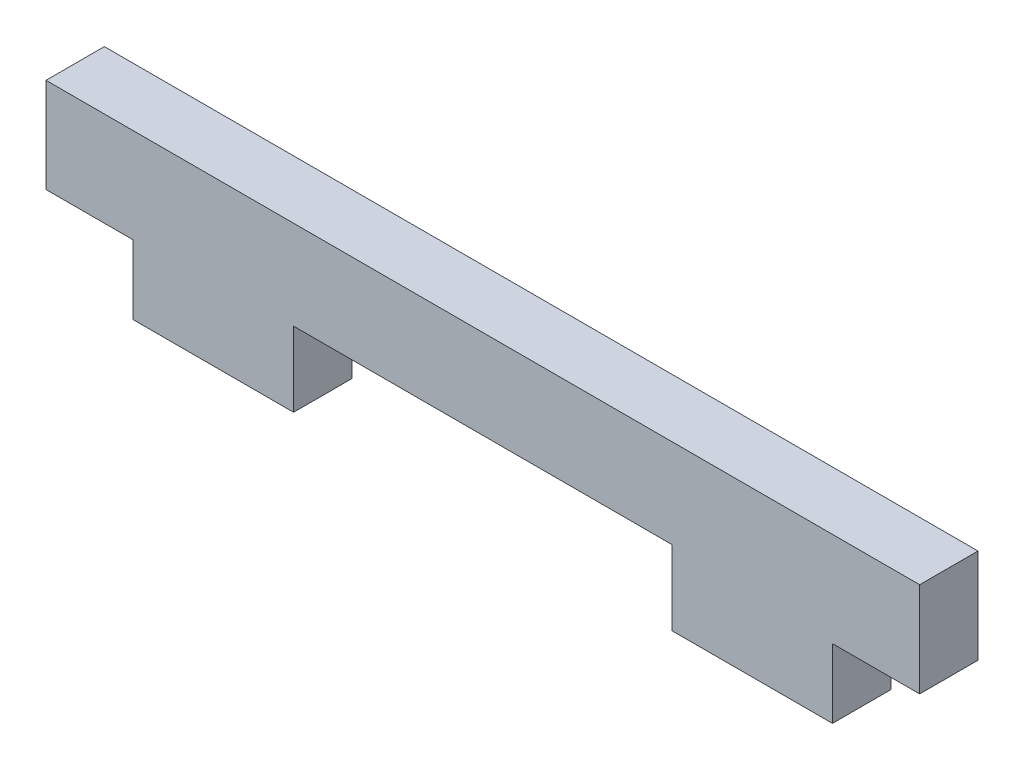
SolidWorks part; units mm, degrees
ref_plane "Front Plane" through (0, 0, 0) normal (0, 0, 1) x (1, 0, 0)
ref_plane "Top Plane" through (0, 0, 0) normal (0, 1, 0) x (1, 0, 0)
ref_plane "Right Plane" through (0, 0, 0) normal (1, 0, 0) x (0, 0, -1)
sketch "Sketch1" plane through (0, 0, 0) normal (0, 0, 1) x (1, 0, 0)
  line L0 (-21.6937, 0) -> (33.7063, 0)
  line L1 (33.7063, 0) -> (33.7063, -6)
  line L2 (33.7063, -6) -> (28.1763, -6)
  line L3 (28.1763, -6) -> (28.1763, -10.3818)
  line L4 (28.1763, -10.3818) -> (18.0063, -10.3818)
  line L5 (18.0063, -10.3818) -> (18.0063, -5.6501)
  line L6 (18.0063, -5.6501) -> (-5.9937, -5.6501)
  line L7 (-5.9937, -5.6501) -> (-5.9937, -10.3818)
  line L8 (-5.9937, -10.3818) -> (-16.1637, -10.3818)
  line L9 (-16.1637, -10.3818) -> (-16.1637, -6)
  line L10 (-16.1637, -6) -> (-21.6937, -6)
  line L11 (-21.6937, -6) -> (-21.6937, 0)
  dimension "D1" = 55.4
  dimension "D2" = 24
  dimension "D3" = 10.17
  dimension "D4" = 6
extrude "Boss-Extrude1" add sketch "Sketch1" along normal blind 3.7
